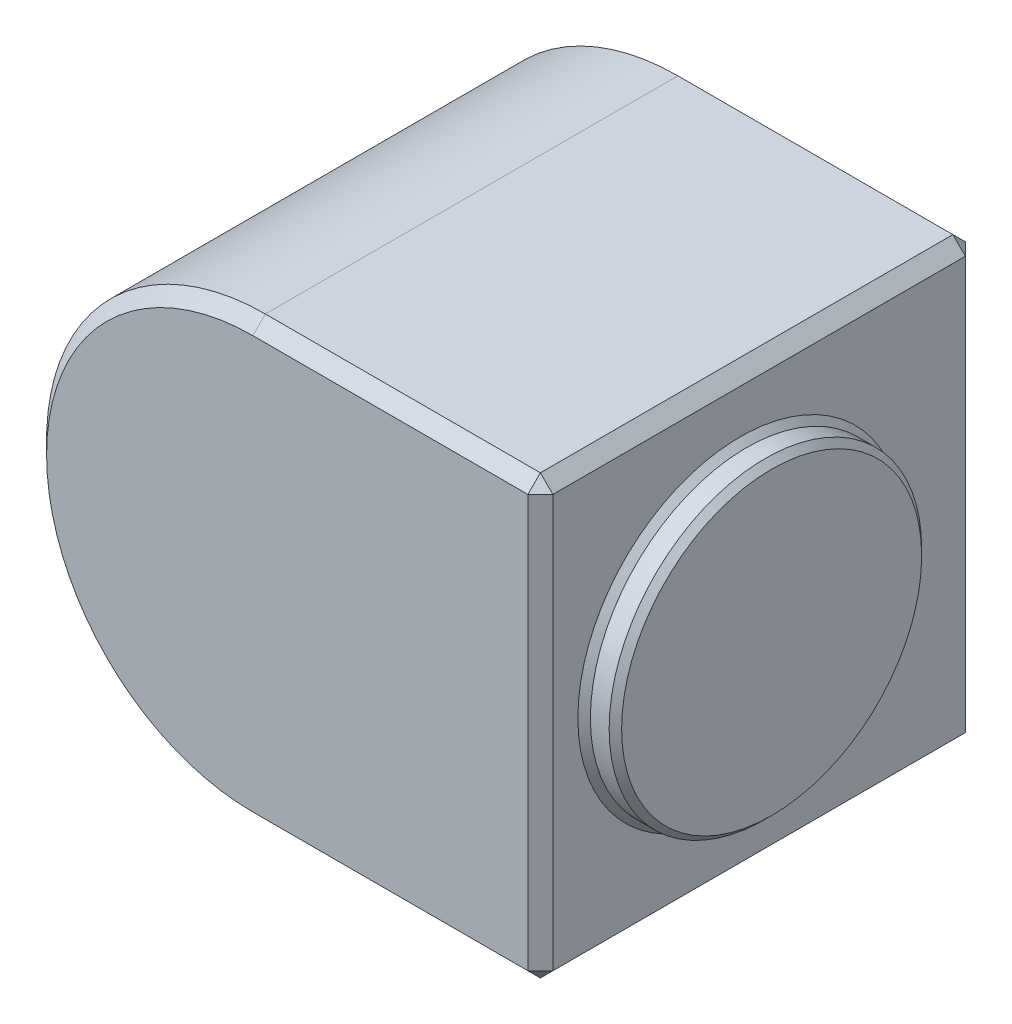
SolidWorks part; units mm, degrees
ref_plane "Front Plane" through (0, 0, 0) normal (0, 0, 1) x (1, 0, 0)
ref_plane "Top Plane" through (0, 0, 0) normal (0, 1, 0) x (1, 0, 0)
ref_plane "Right Plane" through (0, 0, 0) normal (1, 0, 0) x (0, 0, -1)
sketch "Sketch3" plane through (0, 0, 0) normal (0, 0, 1) x (1, 0, 0)
  line L0 (0, 35) -> (46, 35)
  line L1 (46, 35) -> (46, -35)
  line L2 (46, -35) -> (0, -35)
  arc A0 (0, 35) -> (0, -35) centre (0, 0) ccw
  dimension "D1" = 70
  dimension "D2" = 46
extrude "Boss-Extrude1" add sketch "Sketch3" along normal blind 70
sketch "Sketch4" plane through (46, 0, 0) normal (1, 0, 0) x (0, 0, -1)
  line L0 (0, 0) -> (-70, 0) construction
  line L1 (-70, -35) -> (-70, 35) construction
  circle A0 centre (-38, 0) radius 25
  dimension "D1" = 50
  dimension "D2" = 32
extrude "Boss-Extrude2" add sketch "Sketch4" along normal blind 5
sketch "Sketch5" plane through (0, 0, 0) normal (0, 0, -1) x (-1, 0, 0)
  circle A0 centre (0, 0) radius 26
  dimension "D1" = 52
chamfer "Chamfer1" distance 2 angle 45 10 edges at (23, -35, 0) (-35, 0, 0) (23, 35, 0) (46, -35, 35) (46, 0, 0) (46, 35, 35) (23, 35, 70) (46, 0, 70) (23, -35, 70) (-35, 0, 70)
extrude "Cut-Extrude1" cut sketch "Sketch5" against normal blind 5
chamfer "Chamfer3" distance 1 angle 45 4 edges at (-26, 0, 5) (51, 0, 13) (46, 0, 63) (-26, 0, 0)
sketch "Sketch6" plane through (0, 0, 0) normal (0, 1, 0) x (1, 0, 0)
  line L0 (-35, -35) -> (51, -35) construction
  line L1 (-35, -2) -> (-35, -68) construction
  line L2 (51, -62) -> (51, -14) construction
  point P6 (8, -35)
sketch "Sketch7" plane through (0, 0, 0) normal (0, 0, 1) x (1, 0, 0)
  line L0 (0, 56.5456) -> (0, 0) construction
  line L1 (0, 0) -> (65.7436, 0) construction
sketch "Sketch8" plane through (0, 0, 0) normal (0, 1, 0) x (1, 0, 0)
  line L0 (0, 0) -> (0, -91.1786) construction
